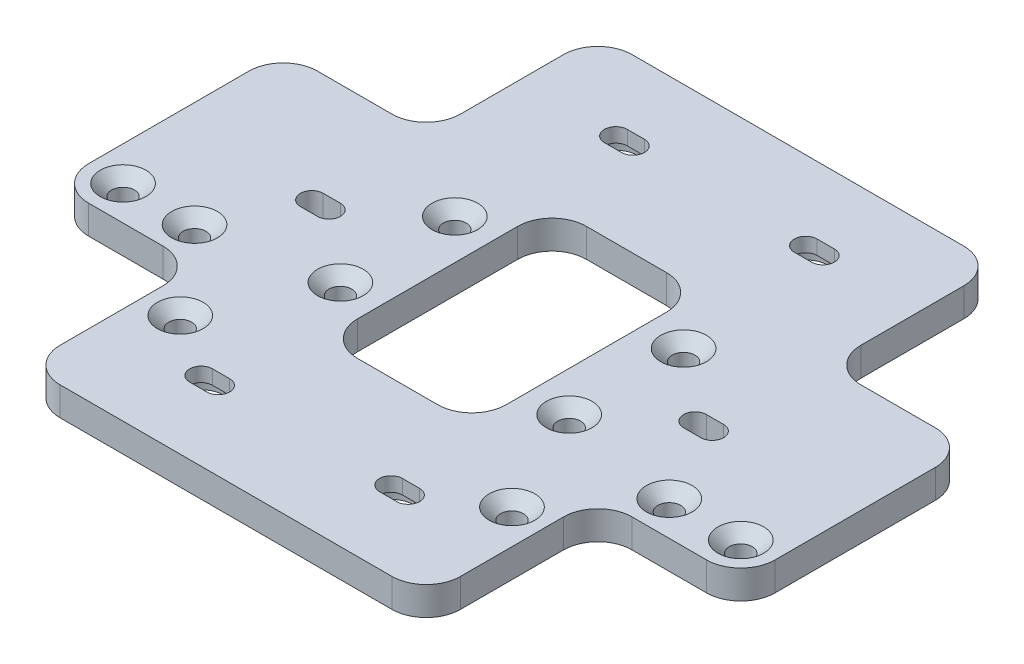
SolidWorks part; units mm, degrees
ref_plane "Plan de face" through (0, 0, 0) normal (0, 0, 1) x (1, 0, 0)
ref_plane "Plan de dessus" through (0, 0, 0) normal (0, 1, 0) x (1, 0, 0)
ref_plane "Plan de droite" through (0, 0, 0) normal (1, 0, 0) x (0, 0, -1)
sketch "Esquisse1" plane through (0, 0, 0) normal (0, 1, 0) x (1, 0, 0)
  line L0 (91.0551, -36.2545) -> (-92.1148, -36.2545) construction
  line L1 (-15.1, -36.2545) -> (-32, 0) construction
  line L2 (-18.1, -36.2545) -> (-35, 0) construction
  line L3 (35, -2) -> (32, -2)
  line L4 (0, 0) -> (-72.9771, 0) construction
  line L5 (13, -14) -> (13, 14)
  line L6 (60, 14) -> (60, -14)
  line L7 (-18.1, -34.2545) -> (-15.1, -34.2545)
  line L8 (-18.1, -38.2545) -> (-15.1, -38.2545)
  line L9 (-29, -50) -> (29, -50)
  line L10 (7, -20) -> (-7, -20)
  line L11 (-13, -14) -> (-13, 14)
  line L12 (0, 0) -> (0, -100) construction
  line L13 (-20, 0) -> (-20, -58.7262) construction
  line L14 (-60, 14) -> (-60, -14)
  line L15 (-35, -44) -> (-35, -26)
  line L16 (-41, -20) -> (-54, -20)
  line L17 (-35, -2) -> (-32, -2)
  line L18 (-35, 2) -> (-32, 2)
  line L19 (35, 2) -> (32, 2)
  line L20 (7, 20) -> (-7, 20)
  line L21 (18.1, -34.2545) -> (15.1, -34.2545)
  line L22 (18.1, -38.2545) -> (15.1, -38.2545)
  line L23 (-41.5, -29) -> (-41.5, -14) construction
  line L24 (-29, 50) -> (29, 50)
  line L25 (-54, -14) -> (-29, -14) construction
  line L26 (-18.1, 38.2545) -> (-15.1, 38.2545)
  line L27 (-18.1, 34.2545) -> (-15.1, 34.2545)
  line L28 (18.1, 38.2545) -> (15.1, 38.2545)
  line L29 (18.1, 34.2545) -> (15.1, 34.2545)
  line L30 (-54, -14) -> (-54, -44) construction
  line L31 (-54, -44) -> (-29, -44) construction
  line L32 (-29, -14) -> (-29, -44) construction
  line L33 (-54, -14) -> (-29, -44) construction
  line L34 (-54, -44) -> (-29, -14) construction
  line L35 (-41.5, -29) -> (-29, -29) construction
  line L36 (35, -44) -> (35, -26)
  line L37 (41, -20) -> (54, -20)
  line L38 (41, 20) -> (54, 20)
  line L39 (35, 44) -> (35, 26)
  line L40 (-35, 44) -> (-35, 26)
  line L41 (-41, 20) -> (-54, 20)
  arc A0 (-35, 2) -> (-35, -2) centre (-35, 0) ccw
  arc A1 (-29, -50) -> (-35, -44) centre (-29, -44) cw
  arc A2 (35, 2) -> (35, -2) centre (35, 0) cw
  arc A3 (32, -2) -> (32, 2) centre (32, 0) cw
  circle A4 centre (-15.1, -36.2545) radius 2 construction
  arc A5 (-18.1, -34.2545) -> (-18.1, -38.2545) centre (-18.1, -36.2545) ccw
  arc A6 (-32, -2) -> (-32, 2) centre (-32, 0) ccw
  circle A7 centre (20, -10) radius 2
  arc A8 (7, -20) -> (13, -14) centre (7, -14) ccw
  arc A9 (15.1, -38.2545) -> (15.1, -34.2545) centre (15.1, -36.2545) cw
  arc A10 (-35, -26) -> (-41, -20) centre (-41, -26) ccw
  arc A11 (-54, -20) -> (-60, -14) centre (-54, -14) cw
  arc A12 (-7, -20) -> (-13, -14) centre (-7, -14) cw
  circle A13 centre (-20, -10) radius 2
  arc A14 (7, 20) -> (13, 14) centre (7, 14) cw
  arc A15 (-7, 20) -> (-13, 14) centre (-7, 14) ccw
  circle A16 centre (-54, -14) radius 2
  arc A17 (18.1, -34.2545) -> (18.1, -38.2545) centre (18.1, -36.2545) cw
  arc A18 (-15.1, 38.2545) -> (-15.1, 34.2545) centre (-15.1, 36.2545) cw
  circle A19 centre (20, 10) radius 2
  circle A20 centre (-20, 10) radius 2
  circle A21 centre (-41.5, -14) radius 2
  circle A23 centre (-29, -29) radius 2
  circle A24 centre (54, -14) radius 2
  arc A25 (-15.1, -38.2545) -> (-15.1, -34.2545) centre (-15.1, -36.2545) ccw
  arc A26 (-18.1, 34.2545) -> (-18.1, 38.2545) centre (-18.1, 36.2545) cw
  arc A27 (18.1, 34.2545) -> (18.1, 38.2545) centre (18.1, 36.2545) ccw
  arc A28 (15.1, 38.2545) -> (15.1, 34.2545) centre (15.1, 36.2545) ccw
  circle A29 centre (41.5, -14) radius 2
  circle A30 centre (29, -29) radius 2
  arc A32 (29, -50) -> (35, -44) centre (29, -44) ccw
  arc A33 (35, -26) -> (41, -20) centre (41, -26) cw
  arc A34 (54, -20) -> (60, -14) centre (54, -14) ccw
  arc A39 (54, 20) -> (60, 14) centre (54, 14) cw
  arc A40 (35, 26) -> (41, 20) centre (41, 26) ccw
  circle A41 centre (0, 0) radius 75 construction
  arc A42 (29, 50) -> (35, 44) centre (29, 44) cw
  arc A43 (-29, 50) -> (-35, 44) centre (-29, 44) ccw
  arc A46 (-35, 26) -> (-41, 20) centre (-41, 26) cw
  arc A49 (-54, 20) -> (-60, 14) centre (-54, 14) ccw
  point P4 (0, 0)
  point P5 (0, 0)
  point P11 (0, 0)
  point P16 (0, 0)
  point P20 (-12, 0)
  point P21 (-12, 0)
  point P22 (0, -10)
  point P27 (0, 0)
  point P35 (16.6, -38.2545)
  point P39 (0, -20)
  point P40 (0, -27.5)
  point P42 (0, -27.5)
  point P43 (0, -20)
  point P46 (0, 0)
  point P47 (0, -50)
  point P48 (0, -27.5)
  point P55 (0, -20)
  point P56 (0, -36.1889)
  point P61 (0, -40.1889)
  point P62 (-35, -50)
  point P63 (0, -50)
  point P70 (0, -50)
  point P78 (13, 0)
  point P83 (-13, 0)
  point P93 (-33.75, -50)
  point P94 (-60, -20)
  point P96 (67.5, 0)
  point P100 (-41.5, -29)
  point P105 (-67.5, 0)
  point P107 (16.6, 38.2545)
  point P144 (0, 0)
  point P147 (0, 0)
  point P162 (0, 0)
  point P163 (-51.0355, 48.5355)
  dimension "D4" = 4
  dimension "D7" = 10
  dimension "D13" = 18.1
  dimension "D6" = 60
  dimension "D9" = 20
  dimension "D2" = 40
  dimension "D10" = 35
  dimension "D11" = 6
  dimension "D14" = 3
  dimension "D18" = 150
  dimension "D3" = 20
  dimension "D5" = 50
  dimension "D8" = 35
  dimension "D12" = 13
extrude "Boss.-Extru.1" add sketch "Esquisse1" along normal blind 5
chamfer "Chanfrein1" distance 2 angle 45 10 edges at (-20, 5, 12) (20, 5, 8) (20, 5, -8) (-20, 5, -12) (54, 5, 12) (41.5, 5, 12) (29, 5, 27) (-29, 5, 31) (-41.5, 5, 16) (-54, 5, 16)
sketch "Esquisse2" plane through (0, 0, 0) normal (0, -1, 0) x (1, 0, 0)
  line L0 (-18.1, -32.2545) -> (-15.1, -32.2545)
  line L1 (-47.799, 0) -> (85.9567, 0) construction
  line L2 (-18.1, -40.2545) -> (-15.1, -40.2545)
  line L3 (0, 50.6732) -> (0, -78.3628) construction
  line L4 (-18.1, 40.2545) -> (-15.1, 40.2545)
  line L5 (-18.1, 32.2545) -> (-15.1, 32.2545)
  line L6 (18.1, 32.2545) -> (15.1, 32.2545)
  line L7 (18.1, 40.2545) -> (15.1, 40.2545)
  line L8 (18.1, -40.2545) -> (15.1, -40.2545)
  line L9 (18.1, -32.2545) -> (15.1, -32.2545)
  arc A0 (-18.1, -32.2545) -> (-18.1, -40.2545) centre (-18.1, -36.2545) ccw
  arc A1 (-15.1, -40.2545) -> (-15.1, -32.2545) centre (-15.1, -36.2545) ccw
  arc A2 (-15.1, -38.2545) -> (-15.1, -34.2545) centre (-15.1, -36.2545) ccw construction
  arc A4 (-15.1, 40.2545) -> (-15.1, 32.2545) centre (-15.1, 36.2545) cw
  arc A5 (-18.1, 32.2545) -> (-18.1, 40.2545) centre (-18.1, 36.2545) cw
  arc A6 (18.1, 32.2545) -> (18.1, 40.2545) centre (18.1, 36.2545) ccw
  arc A7 (15.1, 40.2545) -> (15.1, 32.2545) centre (15.1, 36.2545) ccw
  arc A8 (15.1, -40.2545) -> (15.1, -32.2545) centre (15.1, -36.2545) cw
  arc A9 (18.1, -32.2545) -> (18.1, -40.2545) centre (18.1, -36.2545) cw
  dimension "D1" = 8
extrude "Enlèv. mat.-Extru.1" cut sketch "Esquisse2" against normal blind 2.5
